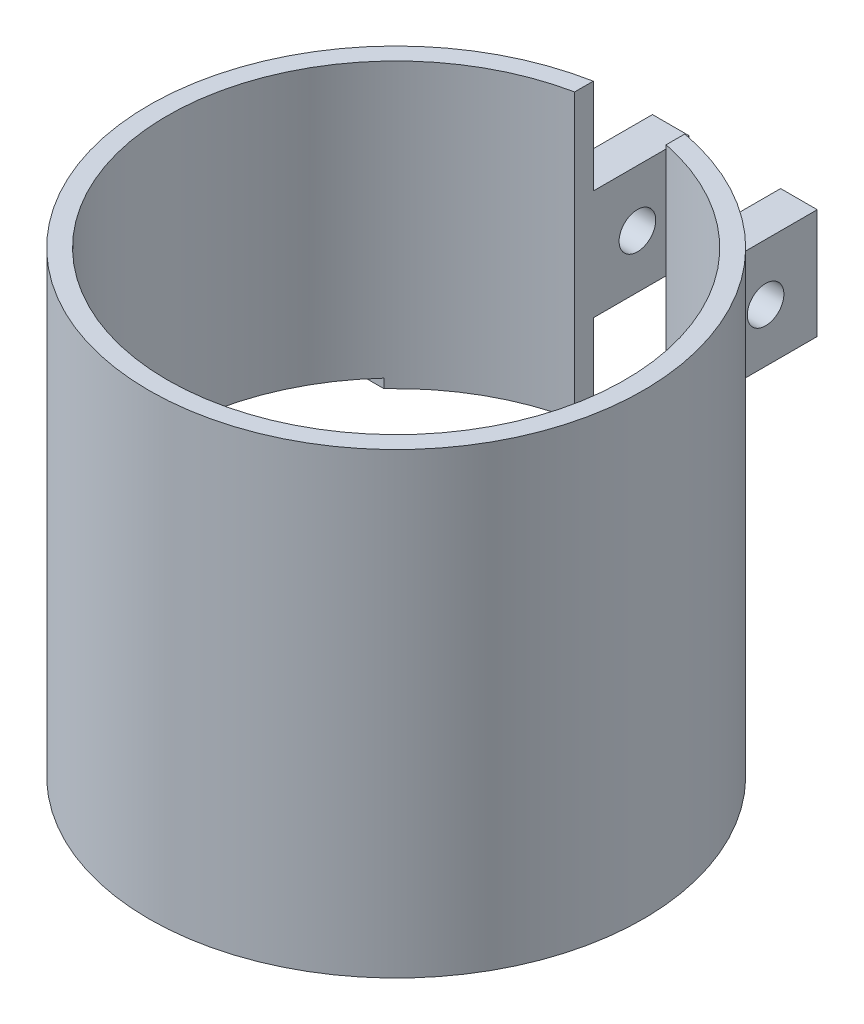
SolidWorks part; units mm, degrees
ref_plane "Front Plane" through (0, 0, 0) normal (0, 0, 1) x (1, 0, 0)
ref_plane "Top Plane" through (0, 0, 0) normal (0, 1, 0) x (1, 0, 0)
ref_plane "Right Plane" through (0, 0, 0) normal (1, 0, 0) x (0, 0, -1)
sketch "Sketch1" plane through (0, 0, 0) normal (0, 1, 0) x (1, 0, 0)
  circle A0 centre (0, 0) radius 13.5
extrude "Boss-Extrude1" add sketch "Sketch1" along normal blind 25
sketch "Sketch2" plane through (0, 25, 0) normal (0, 1, 0) x (1, 0, 0)
  circle A0 centre (0, 0) radius 12.5
extrude "Cut-Extrude1" cut sketch "Sketch2" against normal blind 24
ref_plane "Plane1" through (-13.5, 0, 0) normal (-1, 0, 0) x (0, 0, 1)
sketch "Sketch3" plane through (-13.5, 0, 0) normal (-1, 0, 0) x (0, 0, 1)
  line L0 (0, -2.6122) -> (0, 31.4786) construction
  line L1 (-13.5, 0) -> (13.5, 0) construction
  line L2 (-8.5, 2) -> (8.5, 2)
  line L3 (-8.5, 2) -> (-8.5, 10)
  line L4 (-8.5, 10) -> (8.5, 10)
  line L5 (8.5, 2) -> (8.5, 10)
  line L6 (-8.5, 2) -> (8.5, 10) construction
  line L7 (-8.5, 10) -> (8.5, 2) construction
  point P3 (0, 6)
  dimension "D1" = 8
  dimension "D2" = 17
  dimension "D3" = 2
extrude "Cut-Extrude2" cut sketch "Sketch3" against normal blind 9
ref_plane "Plane2" through (0, 0, -13.5) normal (0, 0, -1) x (-1, 0, 0)
sketch "Sketch4" plane through (0, 0, -13.5) normal (0, 0, -1) x (-1, 0, 0)
  line L0 (0, 27.6538) -> (0, 9.5) construction
  line L2 (2.5, 25) -> (-2.5, 25)
  line L3 (2.5, 25) -> (2.5, 9.5)
  line L4 (-2.5, 25) -> (-2.5, 9.5)
  line L9 (10.5, 9.5) -> (2.5, 9.5)
  line L10 (10.5, 9.5) -> (10.5, 6.5)
  line L11 (10.5, 6.5) -> (-2.5, 6.5)
  line L12 (-2.5, 9.5) -> (-2.5, 6.5)
  line L19 (0, 8.5385) -> (0, -6.6449) construction
  point P3 (0, 16)
  point P10 (4, 7)
  dimension "D1" = 15.5
  dimension "D2" = 5
  dimension "D4" = 3
  dimension "D5" = 13
extrude "Cut-Extrude3" cut sketch "Sketch4" against normal blind 9
sketch "Sketch5" plane through (0, 0, -13.5) normal (0, 0, -1) x (-1, 0, 0)
  line L0 (2.5, 9.5) -> (2.5, 25) construction
  line L1 (4.5, 19.8029) -> (2.5, 19.8029)
  line L2 (4.5, 19.8029) -> (4.5, 13.8029)
  line L3 (4.5, 13.8029) -> (2.5, 13.8029)
  line L4 (2.5, 19.8029) -> (2.5, 13.8029)
  line L5 (4.5, 19.8029) -> (2.5, 13.8029) construction
  line L6 (4.5, 13.8029) -> (2.5, 19.8029) construction
  point P0 (3.5, 16.8029)
  dimension "D1" = 6
  dimension "D2" = 2
extrude "Boss-Extrude2" add sketch "Sketch5" along normal blind 5 and the other way up to surface other way up to face at (0, 1, 12.5)
sketch "Sketch6" plane through (-2.5, 0, 0) normal (1, 0, 0) x (0, 0, -1)
  circle A0 centre (15.6779, 16.7206) radius 1
  dimension "D1" = 2
extrude "Cut-Extrude4" cut sketch "Sketch6" against normal up to surface (2 mm away) up to face at (-4.5, 16.8029, -15.614)
mirror "Mirror1" about plane through (0, 0, 0) normal (1, 0, 0) of "Boss-Extrude2", "Cut-Extrude4"
